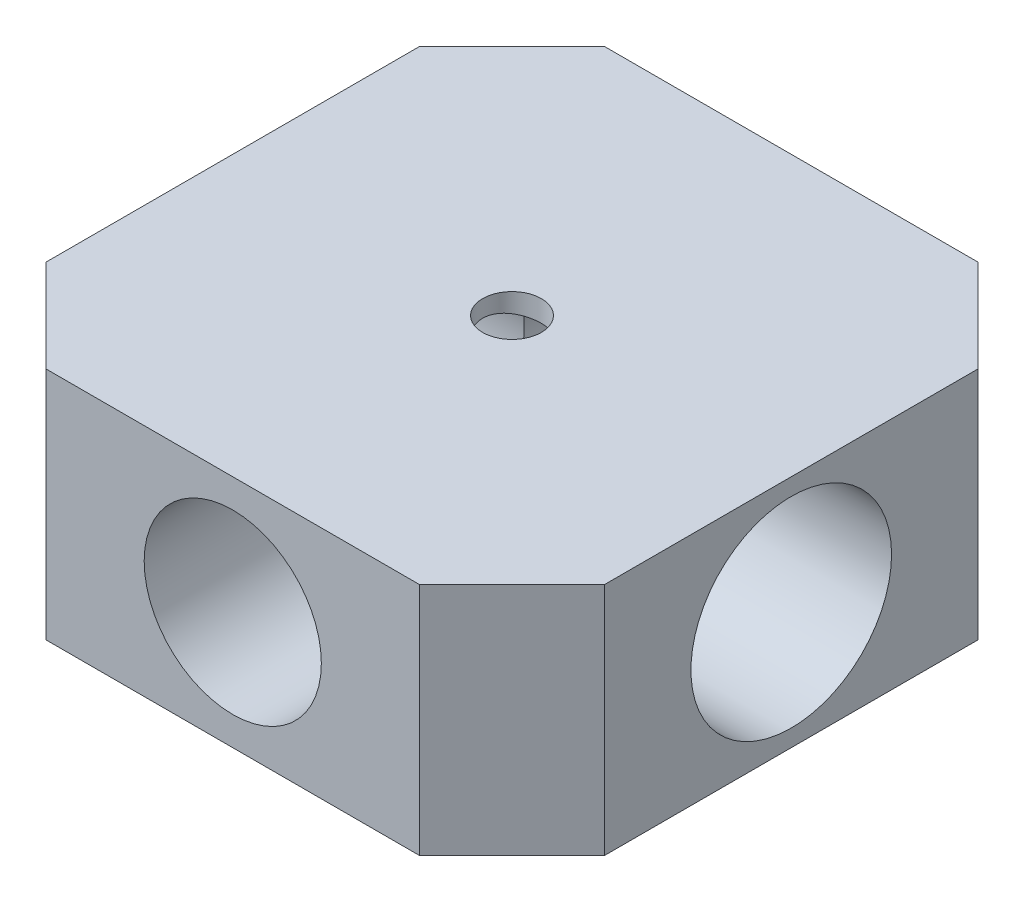
SolidWorks part; units mm, degrees
ref_plane "Front Plane" through (0, 0, 0) normal (0, 0, 1) x (1, 0, 0)
ref_plane "Top Plane" through (0, 0, 0) normal (0, 1, 0) x (1, 0, 0)
ref_plane "Right Plane" through (0, 0, 0) normal (1, 0, 0) x (0, 0, -1)
sketch "Sketch1" plane through (0, 0, 0) normal (0, 1, 0) x (1, 0, 0)
  line L0 (-24, 16) -> (-16, 24)
  line L1 (-16, -24) -> (16, -24)
  line L2 (-24, -16) -> (-24, 16)
  line L3 (-16, 24) -> (16, 24)
  line L4 (24, -16) -> (24, 16)
  line L5 (-24, -24) -> (24, 24) construction
  line L6 (-24, 24) -> (24, -24) construction
  line L7 (-24, -16) -> (-16, -24)
  line L8 (16, -24) -> (24, -16)
  line L9 (16, 24) -> (24, 16)
  point P0 (0, 0)
  dimension "D1" = 48
  dimension "D2" = 48
extrude "Boss-Extrude1" add sketch "Sketch1" along normal blind 20
sketch "Sketch2" plane through (0, 0, 24) normal (0, 0, 1) x (1, 0, 0)
  circle A0 centre (0, 10) radius 7.55
  dimension "D1" = 15.1
extrude "Cut-Extrude1" cut sketch "Sketch2" against normal through all both and the other way through all
sketch "Sketch3" plane through (24, 0, 0) normal (1, 0, 0) x (0, 0, -1)
  circle A0 centre (0, 10) radius 8.55
  dimension "D1" = 17.1
extrude "Cut-Extrude2" cut sketch "Sketch3" against normal through all both and the other way through all
sketch "Sketch4" plane through (0, 20, 0) normal (0, 1, 0) x (1, 0, 0)
  circle A0 centre (0, 0) radius 2.5
  dimension "D1" = 5
extrude "Cut-Extrude3" cut sketch "Sketch4" against normal through all both and the other way through all
sketch "Sketch5" plane through (0, 20, 0) normal (0, 1, 0) x (1, 0, 0)
  line L0 (-24, 16) -> (-24, -16)
  line L1 (-24, -16) -> (-16, -24)
  line L2 (-16, -24) -> (16, -24)
  line L3 (16, -24) -> (24, -16)
  line L4 (24, -16) -> (24, 16)
  line L5 (24, 16) -> (16, 24)
  line L6 (16, 24) -> (-16, 24)
  line L7 (-16, 24) -> (-24, 16)
  line L16 (-23.8, 15.9172) -> (-23.8, -15.9172)
  line L17 (-23.8, -15.9172) -> (-15.9172, -23.8)
  line L18 (-15.9172, -23.8) -> (15.9172, -23.8)
  line L19 (15.9172, -23.8) -> (23.8, -15.9172)
  line L20 (23.8, -15.9172) -> (23.8, 15.9172)
  line L21 (23.8, 15.9172) -> (15.9172, 23.8)
  line L22 (15.9172, 23.8) -> (-15.9172, 23.8)
  line L23 (-15.9172, 23.8) -> (-23.8, 15.9172)
  line L24 (-23.8, 15.9172) -> (-23.8, -15.9172)
  line L25 (-23.8, -15.9172) -> (-15.9172, -23.8)
  line L26 (-15.9172, -23.8) -> (15.9172, -23.8)
  line L27 (15.9172, -23.8) -> (23.8, -15.9172)
  line L28 (23.8, -15.9172) -> (23.8, 15.9172)
  line L29 (23.8, 15.9172) -> (15.9172, 23.8)
  line L30 (15.9172, 23.8) -> (-15.9172, 23.8)
  line L31 (-15.9172, 23.8) -> (-23.8, 15.9172)
  dimension "D1" = 0.2
  dimension "D2" = 0.2
extrude "Cut-Extrude4" cut sketch "Sketch5" against normal through all
